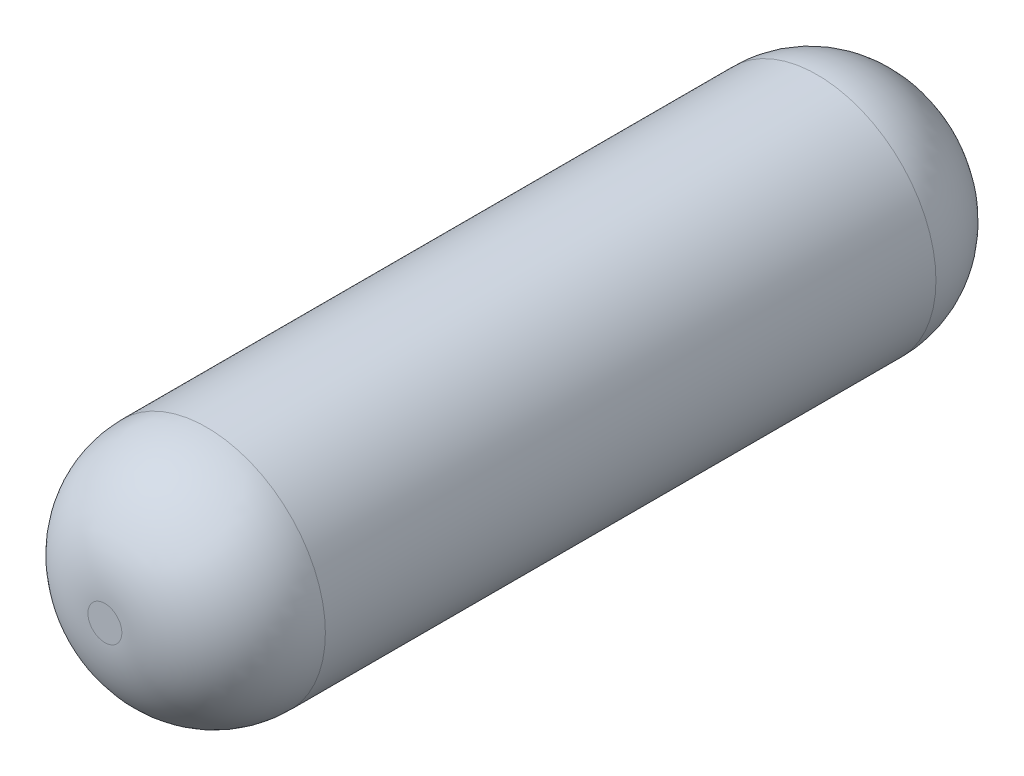
SolidWorks part; units mm, degrees
ref_plane "Front Plane" through (0, 0, 0) normal (0, 0, 1) x (1, 0, 0)
ref_plane "Top Plane" through (0, 0, 0) normal (0, 1, 0) x (1, 0, 0)
ref_plane "Right Plane" through (0, 0, 0) normal (1, 0, 0) x (0, 0, -1)
sketch "Sketch1" plane through (0, 0, 0) normal (0, 0, 1) x (1, 0, 0)
  circle A0 centre (0, 0) radius 35
  dimension "D1" = 70
extrude "Boss-Extrude1" add sketch "Sketch1" along normal blind 240
fillet "Fillet1" radius 30 2 edges at (35, 0, 0) (35, 0, 240)
